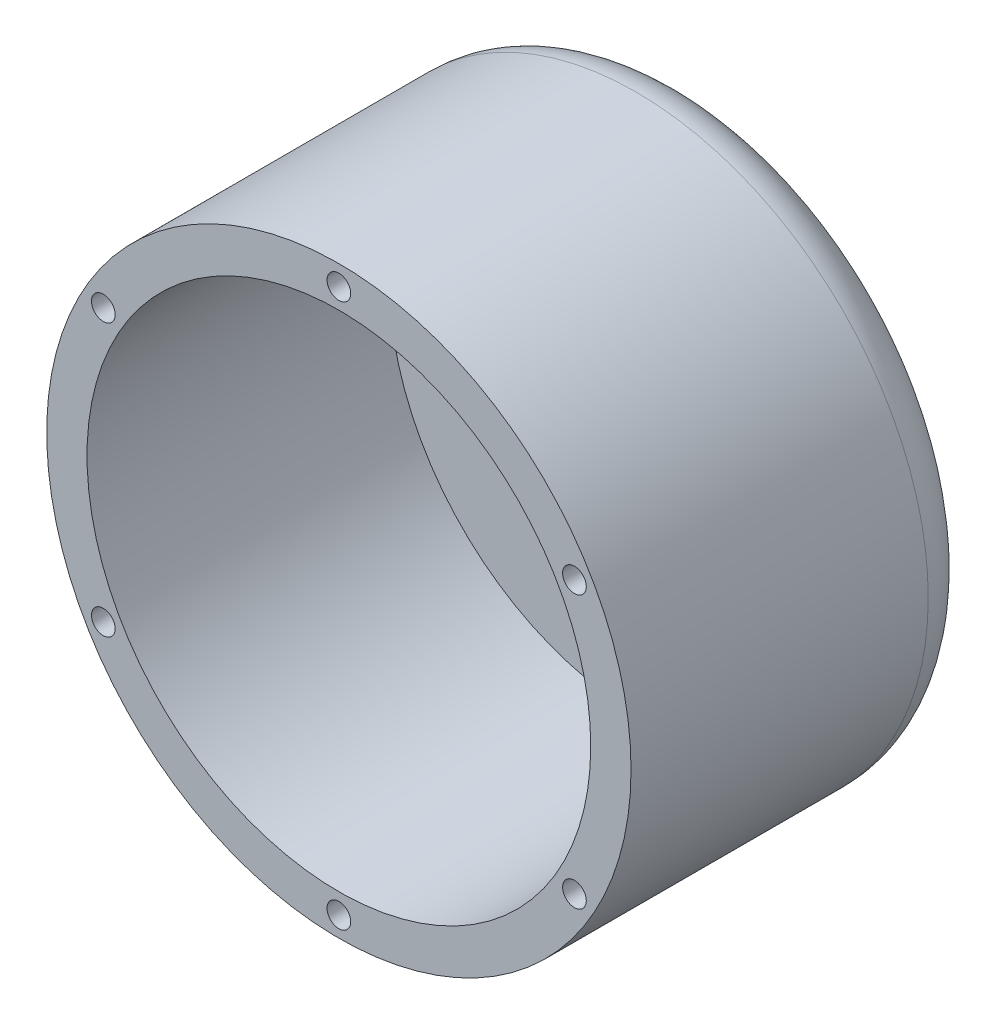
SolidWorks part; units mm, degrees
ref_plane "Front Plane" through (0, 0, 0) normal (0, 0, 1) x (1, 0, 0)
ref_plane "Top Plane" through (0, 0, 0) normal (0, 1, 0) x (1, 0, 0)
ref_plane "Right Plane" through (0, 0, 0) normal (1, 0, 0) x (0, 0, -1)
sketch "Sketch2" plane through (0, 0, 0) normal (0, 1, 0) x (1, 0, 0)
  line L0 (0, -1000) -> (0, 49000) construction
  line L1 (58, 0) -> (50, 0)
  line L2 (58, 0) -> (58, 60)
  line L3 (58, 60) -> (50, 60)
  line L4 (50, 0) -> (50, 60)
  line L5 (50, 60) -> (58, 60)
  line L6 (50, 60) -> (50, 69)
  line L7 (50, 69) -> (58, 69)
  line L8 (58, 60) -> (58, 69)
  line L10 (50, 60) -> (0, 60)
  line L11 (50, 60) -> (50, 69)
  line L12 (50, 69) -> (0, 69)
  line L13 (0, 60) -> (0, 69)
  dimension "D1" = 60
  dimension "D2" = 8
  dimension "D3" = 50
  dimension "D4" = 0
  dimension "D5" = 9
revolve "Revolve1" add sketch "Sketch2" angle 360 about L0
sketch "Sketch3" plane through (0, 0, 0) normal (0, 0, 1) x (1, 0, 0)
  circle A0 centre (0, 54) radius 4 construction
  circle A1 centre (46.7654, 27) radius 2.35
  circle A2 centre (0, 0) radius 50 construction
  circle A3 centre (0, 0) radius 58 construction
  circle A4 centre (0, 54) radius 2.35
  circle A5 centre (46.7654, -27) radius 2.35
  circle A6 centre (0, -54) radius 2.35
  circle A7 centre (-46.7654, -27) radius 2.35
  circle A8 centre (-46.7654, 27) radius 2.35
  point P20 (0, 0)
  dimension "D1" = 4.7
  dimension "D2" = 6
extrude "Cut-Extrude1" cut sketch "Sketch3" against normal blind 6
sketch "Sketch4" plane through (0, 0, -69) normal (0, 0, -1) x (-1, 0, 0)
  line L0 (15, -998.4304) -> (15, 49001.5696) construction
  line L1 (-33, -1003.5603) -> (-33, 48996.4397) construction
  line L2 (-1000, 0) -> (49000, 0) construction
  line L3 (-9, 11.2301) -> (-9, -9.9243) construction
  line L5 (-29.5, 10) -> (11.5, 10)
  line L6 (-29.5, 10) -> (-29.5, -10)
  line L7 (-29.5, -10) -> (11.5, -10)
  line L8 (11.5, 10) -> (11.5, -10)
  circle A0 centre (0, 0) radius 7 construction
  circle A1 centre (15, 5) radius 1.5
  circle A2 centre (15, -5) radius 1.5
  circle A3 centre (-33, -5) radius 1.5
  circle A4 centre (-33, 5) radius 1.5
  dimension "D1" = 14
  dimension "D2" = 15
  dimension "D3" = 3
  dimension "D4" = 5
  dimension "D5" = 48
  dimension "D6" = 24
  dimension "D7" = 41
  dimension "D8" = 20
  dimension "D9" = 10
  dimension "D10" = 3.5
extrude "Cut-Extrude2" cut sketch "Sketch4" against normal up to next
fillet "Fillet1" radius 10 1 edges at (58, 0, -69)
